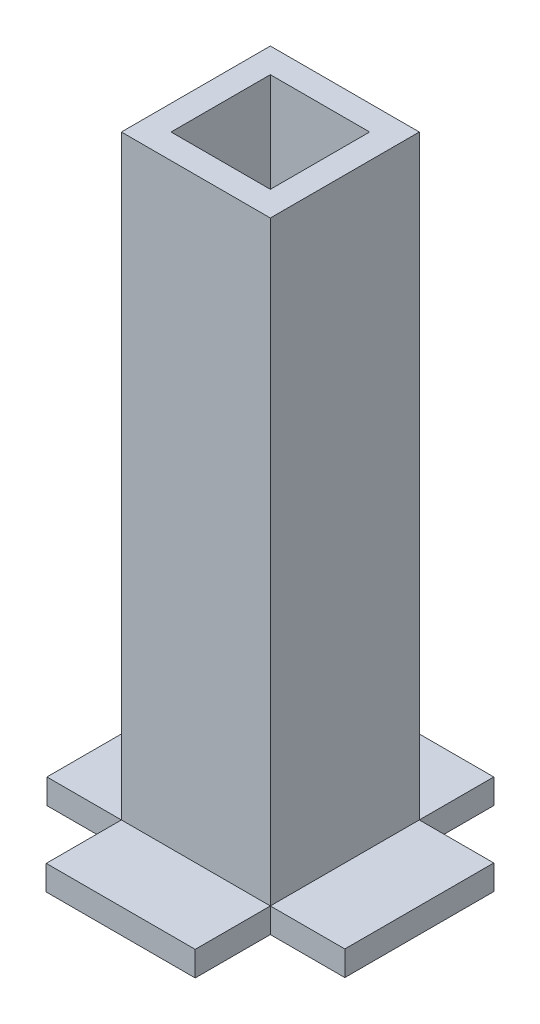
SolidWorks part; units mm, degrees
ref_plane "Plan de face" through (0, 0, 0) normal (0, 0, 1) x (1, 0, 0)
ref_plane "Plan de dessus" through (0, 0, 0) normal (0, 1, 0) x (1, 0, 0)
ref_plane "Plan de droite" through (0, 0, 0) normal (1, 0, 0) x (0, 0, -1)
sketch "Esquisse1" plane through (0, 0, 0) normal (0, 1, 0) x (1, 0, 0)
  line L1 (0, 0) -> (60, 0)
  line L2 (0, 0) -> (0, 60)
  line L3 (0, 60) -> (60, 60)
  line L4 (60, 0) -> (60, 60)
extrude "Boss.-Extru.1" add sketch "Esquisse1" along normal blind 250 contours L2 L1 L4 L3
sketch "Esquisse2" plane through (0, 250, 0) normal (0, 1, 0) x (1, 0, 0)
  line L1 (10, 50) -> (50, 50)
  line L2 (10, 50) -> (10, 10)
  line L3 (10, 10) -> (50, 10)
  line L4 (50, 50) -> (50, 10)
extrude "Enlèv. mat.-Extru.1" cut sketch "Esquisse2" against normal blind 250 contours L2 L1 L4 L3
sketch "Esquisse3" plane through (0, 0, 0) normal (1, 0, 0) x (0, 0, -1)
  line L5 (40, 170) -> (20, 170)
  line L6 (40, 170) -> (40, 129)
  line L7 (40, 129) -> (20, 129)
  line L8 (20, 170) -> (20, 129)
  line L13 (0, 250) -> (60, 250) construction
  line L14 (60, 250) -> (60, 0) construction
  line L15 (0, 33) -> (0, -33) construction
  point P0 (0, 0)
  dimension "D1" = 80
  dimension "D2" = 20
  dimension "D3" = 121
  dimension "D4" = 20
extrude "Enlèv. mat.-Extru.7" cut sketch "Esquisse3" along normal blind 10
sketch "Esquisse4" plane through (0, 0, 0) normal (0, 1, 0) x (1, 0, 0)
  line L0 (0, -30.275) -> (60, -30.275)
  line L1 (0, 60) -> (60, 60)
  line L2 (0, 60) -> (0, 90)
  line L3 (0, 90) -> (60, 90)
  line L4 (60, 60) -> (60, 90)
  line L5 (0, -30.275) -> (0, 0)
  line L6 (0, 0) -> (60, 0)
  line L7 (60, -30.275) -> (60, 0)
  line L12 (-33, 0) -> (33, 0) construction
  line L13 (60, 60) -> (90, 60)
  line L14 (60, 60) -> (60, 0)
  line L15 (60, 0) -> (90, 0)
  line L16 (90, 60) -> (90, 0)
  line L22 (0, 60) -> (-30, 60)
  line L23 (0, 60) -> (0, 0)
  line L24 (0, 0) -> (-30, 0)
  line L25 (-30, 60) -> (-30, 0)
extrude "Boss.-Extru.2" add sketch "Esquisse4" along normal blind 10 contours L1 L4 L3 L2 | L22 L25 L24 L23 | L16 L13 L14 L15 | L0 L7 L6 L5
sketch "Esquisse6" plane through (0, 0, 0) normal (-1, 0, 0) x (0, 0, 1)
  line L0 (-40, 170) -> (-20, 170) construction
  line L1 (-20, 170) -> (-20, 129) construction
  line L2 (-40, 129) -> (-40, 170) construction
  line L3 (-20, 129) -> (-40, 129) construction
  circle A0 centre (-34.5, 173.5) radius 2
  circle A1 centre (-25.5, 173.5) radius 2
  circle A2 centre (-34.5, 125.5) radius 2
  circle A3 centre (-25.5, 125.5) radius 2
  point P4 (0, 0)
  point P8 (0, 0)
  point P9 (0, 0)
  point P10 (-20, 170)
  point P11 (0, 0)
  point P14 (0, 0)
  point P21 (0, 0)
  dimension "D1" = 3.5
  dimension "D2" = 4
  dimension "D4" = 4
  dimension "D7" = 5.5
  dimension "D11" = 4
  dimension "D12" = 4
  dimension "D3" = 5.5
  dimension "D5" = 3.5
  dimension "D6" = 5.5
  dimension "D8" = 5.5
  dimension "D9" = 3.5
  dimension "D10" = 3.5
extrude "Enlèv. mat.-Extru.8" cut sketch "Esquisse6" against normal blind 10
